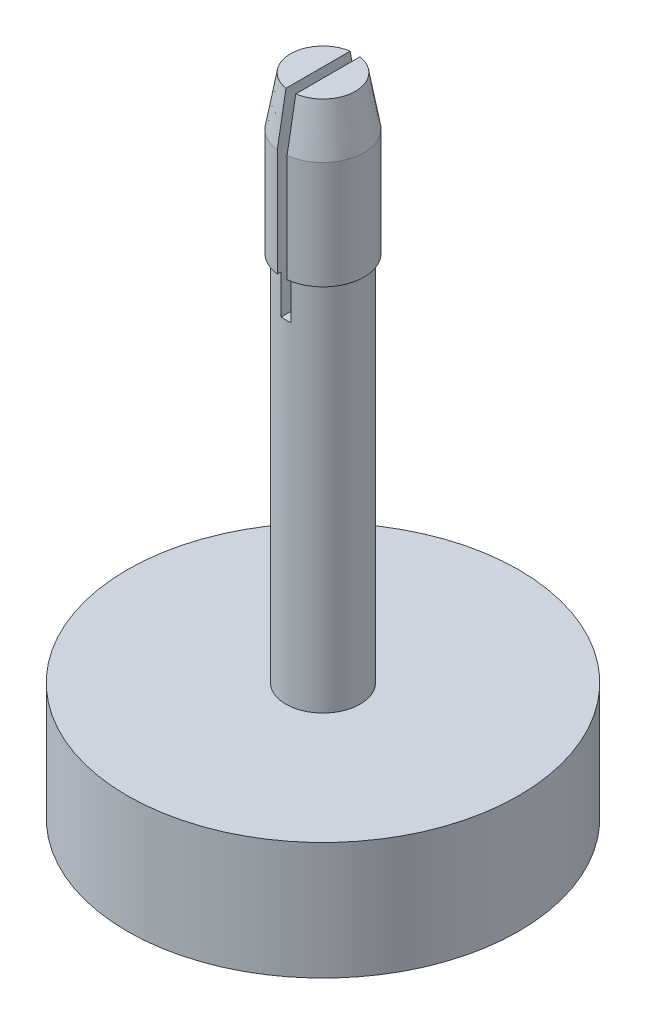
SolidWorks part; units mm, degrees
ref_plane "Plan de face" through (0, 0, 0) normal (0, 0, 1) x (1, 0, 0)
ref_plane "Plan de dessus" through (0, 0, 0) normal (0, 1, 0) x (1, 0, 0)
ref_plane "Plan de droite" through (0, 0, 0) normal (1, 0, 0) x (0, 0, -1)
sketch "Esquisse2" plane through (0, 0, 0) normal (0, 1, 0) x (1, 0, 0)
  circle A0 centre (0, 0) radius 5
extrude "Boss.-Extru.1" add sketch "Esquisse2" along normal blind 3
sketch "Esquisse3" plane through (0, 3, 0) normal (0, 1, 0) x (1, 0, 0)
  circle A0 centre (0, 0) radius 0.95
  dimension "D1" = 1.9
extrude "Boss.-Extru.2" add sketch "Esquisse3" along normal blind 9.5
ref_plane "Plan1" through (0, 12.5, 0) normal (0, 1, 0) x (1, 0, 0)
sketch "Esquisse4" plane through (0, 12.5, 0) normal (0, 1, 0) x (1, 0, 0)
  circle A0 centre (0, 0) radius 1.05
  dimension "D1" = 2.1
extrude "Boss.-Extru.3" add sketch "Esquisse4" along normal blind 4
chamfer "Chanfrein3" distance 1.25 angle 10 1 edges at (0, 16.5, 1.05)
sketch "Esquisse5" plane through (0, 16.5, 0) normal (0, 1, 0) x (1, 0, 0)
  line L1 (0.125, 1.5) -> (-0.125, 1.5)
  line L2 (0.125, 1.5) -> (0.125, -1.5)
  line L3 (0.125, -1.5) -> (-0.125, -1.5)
  line L4 (-0.125, 1.5) -> (-0.125, -1.5)
  line L5 (0.125, 1.5) -> (-0.125, -1.5) construction
  line L6 (0.125, -1.5) -> (-0.125, 1.5) construction
  point P0 (0, 0)
  dimension "D1" = 0.25
  dimension "D2" = 3
extrude "Enlèv. mat.-Extru.1" cut sketch "Esquisse5" against normal blind 5
